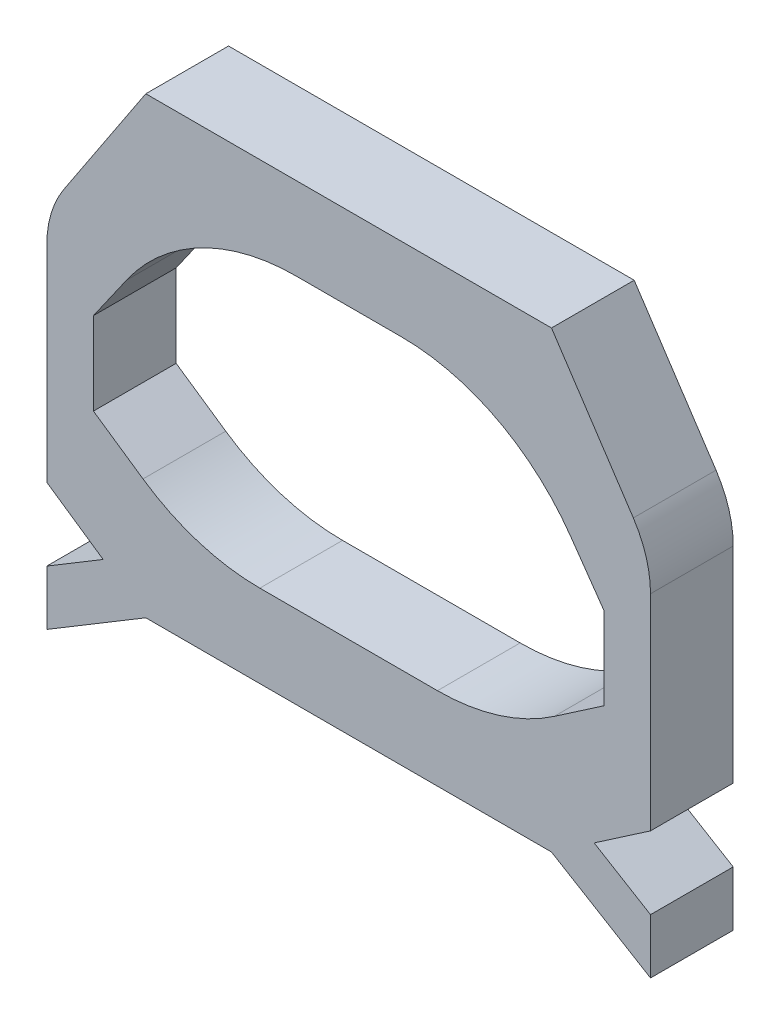
SolidWorks part; units mm, degrees
material "ABS"
ref_plane "Front Plane" through (0, 0, 0) normal (0, 0, 1) x (1, 0, 0)
ref_plane "Top Plane" through (0, 0, 0) normal (0, 1, 0) x (1, 0, 0)
ref_plane "Right Plane" through (0, 0, 0) normal (1, 0, 0) x (0, 0, -1)
sketch "Sketch1" plane through (0, 0, 132.6107) normal (0, 0, 1) x (1, 0, 0)
  line L3 (-83.5786, 26.563) -> (-83.5786, 12.0342)
  line L4 (-83.5786, 26.563) -> (-9.2074, 26.563) construction
  line L6 (-71.4121, 59.4567) -> (-21.5772, 59.4567)
  line L7 (-65.2666, 13.863) -> (-77.8465, 22.4773)
  line L8 (-65.2666, 13.863) -> (-27.7227, 13.863)
  line L9 (-46.4946, -4.2179) -> (-46.4946, 77.1103) construction
  line L10 (-21.5772, 3.703) -> (-71.4121, 3.703)
  line L11 (-77.8465, 32.6373) -> (-77.8465, 22.4773)
  line L12 (-15.1428, 32.6373) -> (-15.1428, 22.4773)
  line L15 (-71.4121, 3.703) -> (-83.5786, 12.0342)
  line L16 (-9.4106, 41.0868) -> (-21.5772, 59.4567)
  line L17 (-15.1428, 32.6373) -> (-26.8078, 49.2967)
  line L18 (-9.4106, 26.563) -> (-9.4106, 41.0868)
  line L19 (-83.5786, 26.563) -> (-83.5786, 41.0868)
  line L20 (-9.4106, 26.563) -> (-9.4106, 12.0342)
  line L21 (-21.5772, 3.703) -> (-9.4106, 12.0342)
  line L22 (-27.7227, 13.863) -> (-15.1428, 22.4773)
  line L23 (-83.5786, 41.0868) -> (-71.4121, 59.4567)
  line L26 (-66.1815, 49.2967) -> (-26.8078, 49.2967)
  line L27 (-77.8465, 32.6373) -> (-66.1815, 49.2967)
  point P1 (-46.4946, 49.2967)
  point P4 (-46.4946, 31.643)
  point P5 (-46.4946, 32.6373)
  point P7 (-46.4946, 36.4462)
  point P18 (-46.4946, 59.4567)
  point P22 (-46.4946, 22.4773)
  point P26 (-46.4946, 13.863)
  point P35 (-46.4946, 59.4567)
  point P41 (-46.4946, 3.703)
  dimension "D3" = 14.5238
  dimension "D6" = 0
  dimension "D7" = 37.084
extrude "Boss-Extrude1" add sketch "Sketch1" against normal blind 5.08 and the other way blind 5.08 from offset 15.3035 offset against normal yes
fillet "Fillet1" radius 12.7 1 edges at (-9.4106, 41.0868, 117.3072)
fillet "Fillet2" radius 12.7 1 edges at (-83.5786, 41.0868, 117.3072)
fillet "Fillet3" radius 25.4 4 edges at (-65.2666, 13.863, 117.3072) (-27.7227, 13.863, 117.3072) (-26.8078, 49.2967, 117.3072) (-66.1815, 49.2967, 117.3072)
sketch "Sketch2" plane through (0, 0, 122.3872) normal (0, 0, 1) x (1, 0, 0)
  line L0 (-83.5786, -3.6172) -> (-71.4121, 3.703)
  line L1 (-71.4121, 3.703) -> (-76.6515, 7.2908)
  line L2 (-71.4121, 3.703) -> (-83.5786, 12.0342) construction
  line L3 (-76.6515, 7.2908) -> (-83.5786, 3.1229)
  line L4 (-83.5786, -3.6172) -> (-83.5786, 37.9118) construction
  line L5 (-83.5786, 3.1229) -> (-83.5786, -3.6172)
  dimension "D1" = 6.35
extrude "Boss-Extrude2" add sketch "Sketch2" against normal blind 10.16
ref_plane "Plane1" through (-46.4946, 0, 0) normal (1, 0, 0) x (0, 0, -1)
mirror "Mirror1" about plane through (-46.4946, 0, 0) normal (1, 0, 0) of "Boss-Extrude2"
ref_plane "Plane2" through (0, 0, 117.3072) normal (0, 0, -1) x (-1, 0, 0)
sketch "Sketch3" plane through (0, 0, 117.3072) normal (0, 0, -1) x (-1, 0, 0)
  line L0 (24.891, 56.4567) -> (68.2188, 56.4567)
  line L1 (68.2188, 56.4567) -> (79.0166, 39.5865)
  line L2 (79.0166, 39.5865) -> (68.2188, 52.2967)
  line L3 (68.2188, 52.2967) -> (24.891, 52.2967)
  line L4 (71.4121, 59.4567) -> (21.5772, 59.4567) construction
  line L5 (52.959, 49.2967) -> (40.0302, 49.2967) construction
  line L6 (46.5549, 38.3957) -> (46.5549, 72.1608) construction
  line L7 (79.0166, 19.0366) -> (79.0166, 12.8571)
  line L8 (79.0166, 12.8571) -> (70.1215, 6.703)
  line L9 (70.1215, 6.703) -> (22.9883, 6.703)
  line L10 (79.0166, 19.0366) -> (67.0802, 10.863)
  line L11 (67.0802, 10.863) -> (26.0296, 10.863)
  line L12 (57.4035, 13.863) -> (35.5858, 13.863) construction
  line L13 (21.5772, 3.703) -> (71.4121, 3.703) construction
  line L14 (76.6515, 7.2908) -> (83.5786, 12.0342) construction
  line L15 (71.7543, 18.3056) -> (77.8465, 22.4773) construction
  line L16 (14.0932, 19.0366) -> (14.0932, 12.8571)
  line L17 (14.0932, 12.8571) -> (22.9883, 6.703)
  line L18 (14.0932, 19.0366) -> (26.0296, 10.863)
  line L19 (14.0932, 39.5865) -> (24.891, 52.2967)
  line L20 (24.891, 56.4567) -> (14.0932, 39.5865)
  point P0 (46.5549, 52.2967)
  point P21 (80.115, 9.6625)
  point P27 (46.5549, 6.703)
  point P28 (46.5549, 10.863)
  point P33 (46.5549, 56.4567)
  dimension "D1" = 3
  dimension "D2" = 3
  dimension "D3" = 3
  dimension "D4" = 3
  dimension "D5" = 3.2521
  dimension "D7" = 3.5
extrude "Cut-Extrude1" cut sketch "Sketch3" against normal blind 2.032 and the other way blind 2.032
